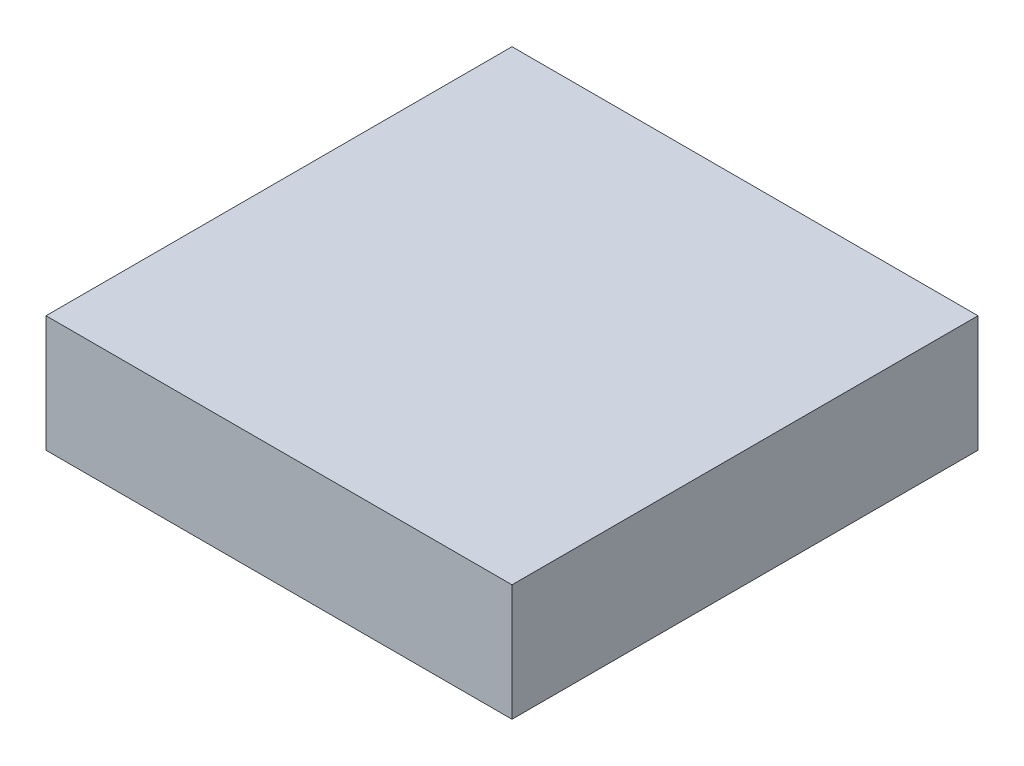
SolidWorks part; units mm, degrees
ref_plane "Front Plane" through (0, 0, 0) normal (0, 0, 1) x (1, 0, 0)
ref_plane "Top Plane" through (0, 0, 0) normal (0, 1, 0) x (1, 0, 0)
ref_plane "Right Plane" through (0, 0, 0) normal (1, 0, 0) x (0, 0, -1)
sketch "Sketch1" plane through (0, 0, 0) normal (0, 1, 0) x (1, 0, 0)
  line L1 (0, 0) -> (20, 0)
  line L2 (0, 0) -> (0, 20)
  line L3 (0, 20) -> (20, 20)
  line L4 (20, 0) -> (20, 20)
  dimension "D1" = 20
  dimension "D2" = 20
extrude "Boss-Extrude1" add sketch "Sketch1" along normal blind 5
